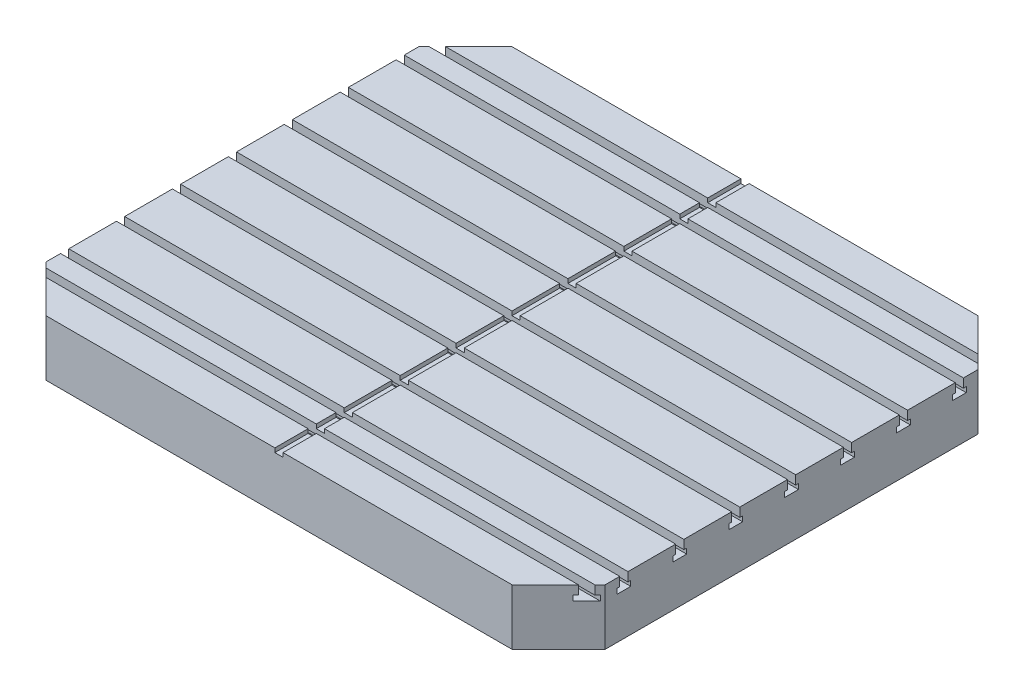
SolidWorks part; units mm, degrees
ref_plane "Front Plane" through (0, 0, 0) normal (0, 0, 1) x (1, 0, 0)
ref_plane "Top Plane" through (0, 0, 0) normal (0, 1, 0) x (1, 0, 0)
ref_plane "Right Plane" through (0, 0, 0) normal (1, 0, 0) x (0, 0, -1)
sketch "Sketch1" plane through (0, 0, 0) normal (0, 1, 0) x (1, 0, 0)
  line L1 (-750, -625) -> (750, -625)
  line L2 (-750, -625) -> (-750, 625)
  line L3 (-750, 625) -> (750, 625)
  line L4 (750, -625) -> (750, 625)
  line L5 (-750, -625) -> (750, 625) construction
  line L6 (-750, 625) -> (750, -625) construction
  point P0 (0, 0)
  dimension "D1" = 1500
  dimension "D2" = 1250
extrude "Boss-Extrude1" add sketch "Sketch1" against normal blind 150
sketch "Sketch2" plane through (750, 0, 0) normal (1, 0, 0) x (0, 0, -1)
  line L0 (0, 10.9914) -> (0, 36.6723) construction
  line L1 (-625, 0) -> (625, 0) construction
  line L2 (-11, 0) -> (11, 0)
  line L3 (-11, 0) -> (-11, -24)
  line L4 (-11, -24) -> (-18.5, -24)
  line L5 (-18.5, -24) -> (-18.5, -38)
  line L6 (-18.5, -38) -> (18.5, -38)
  line L7 (18.5, -38) -> (18.5, -24)
  line L8 (18.5, -24) -> (11, -24)
  line L9 (11, -24) -> (11, 0)
  dimension "D1" = 22
  dimension "D2" = 37
  dimension "D3" = 38
  dimension "D4" = 24
extrude "Cut-Extrude1" cut sketch "Sketch2" against normal up to next
pattern_linear "LPattern1" count 4 spacing 150 along (0, 0, -1) count 4 spacing 150 along (0, 0, 1) of "Cut-Extrude1"
sketch "Sketch3" plane through (0, 0, -625) normal (0, 0, -1) x (-1, 0, 0)
  line L0 (0, 68.7815) -> (0, 214.2207) construction
  line L1 (-750, 0) -> (750, 0) construction
  line L2 (-11, 0) -> (11, 0)
  line L3 (-11, 0) -> (-11, -11)
  line L4 (-11, -11) -> (11, -11)
  line L5 (11, -11) -> (11, 0)
  dimension "D1" = 22
  dimension "D2" = 11
extrude "Cut-Extrude2" cut sketch "Sketch3" against normal up to surface (1250 mm away) up to face at (0, -75, 625)
pattern_linear "LPattern2" count 2 spacing 525 along (0, 0, -1) count 2 spacing 525 along (0, 0, 1) of "Cut-Extrude1"
chamfer "Chamfer1" distance 125 angle 45 4 edges at (-750, -75, 625) (-750, -75, -625) (750, -75, -625) (750, -75, 625)
